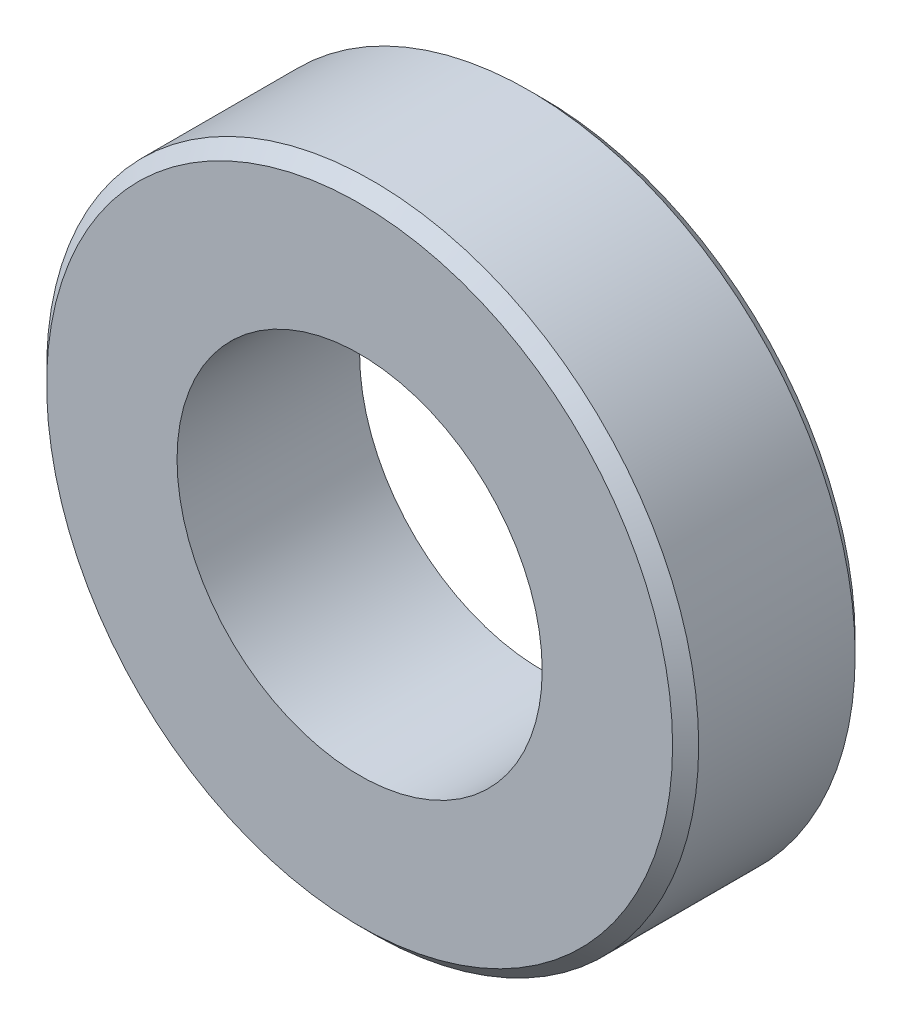
SolidWorks part; units mm, degrees
ref_plane "前基準面" through (0, 0, 0) normal (0, 0, 1) x (1, 0, 0)
ref_plane "上基準面" through (0, 0, 0) normal (0, 1, 0) x (1, 0, 0)
ref_plane "右基準面" through (0, 0, 0) normal (1, 0, 0) x (0, 0, -1)
sketch "草圖1" plane through (0, 0, 0) normal (0, 0, 1) x (1, 0, 0)
  circle A0 centre (0, 0) radius 7
  circle A1 centre (0, 0) radius 12.5
  dimension "D1" = 14
  dimension "D2" = 25
extrude "填料-伸長1" add sketch "草圖1" along normal blind 7
chamfer "導角1" distance 0.5 angle 45 2 edges at (12.5, 0, 0) (12.5, 0, 7)
